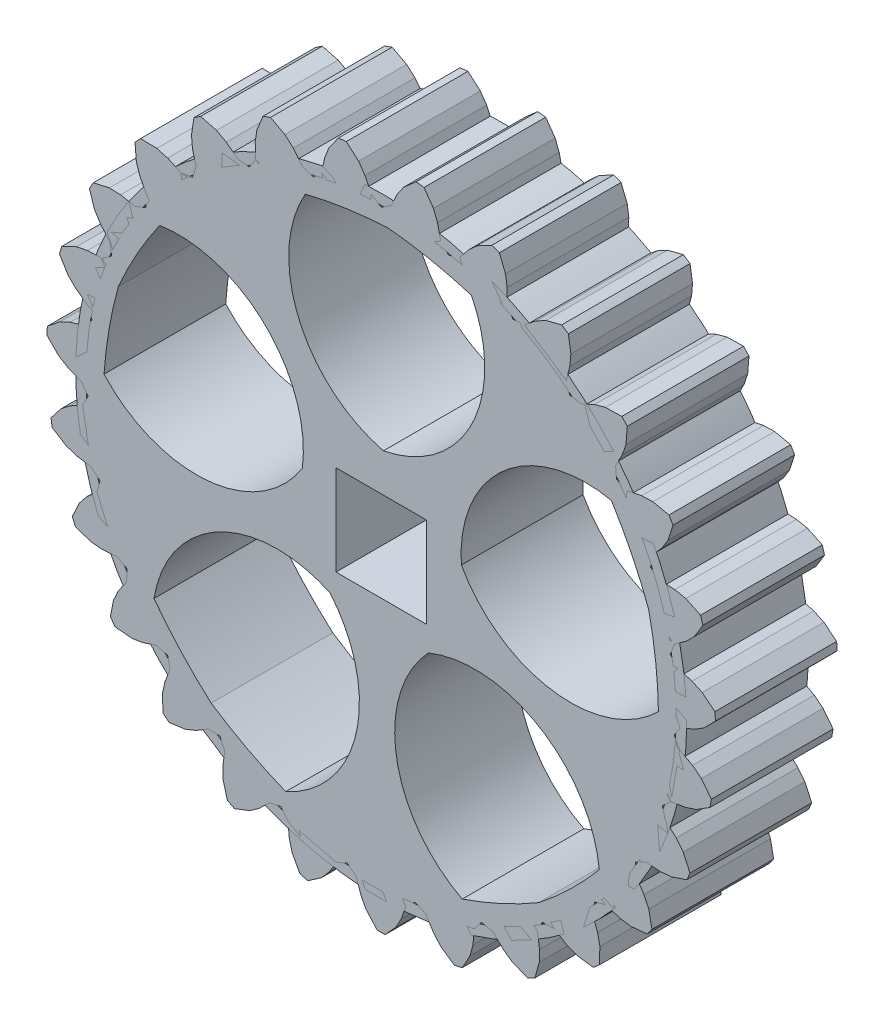
SolidWorks part; units mm, degrees
ref_plane "Front Plane" through (0, 0, 0) normal (0, 0, 1) x (1, 0, 0)
ref_plane "Top Plane" through (0, 0, 0) normal (0, 1, 0) x (1, 0, 0)
ref_plane "Right Plane" through (0, 0, 0) normal (1, 0, 0) x (0, 0, -1)
sketch "Sketch1" plane through (0, 0, 0) normal (0, 0, 1) x (1, 0, 0)
  line L1 (3.7123, -3.7123) -> (-3.7123, -3.7123)
  line L2 (3.7123, -3.7123) -> (3.7123, 3.7123)
  line L3 (3.7123, 3.7123) -> (-3.7123, 3.7123)
  line L4 (-3.7123, -3.7123) -> (-3.7123, 3.7123)
  line L5 (3.7123, -3.7123) -> (-3.7123, 3.7123) construction
  line L6 (3.7123, 3.7123) -> (-3.7123, -3.7123) construction
  circle A0 centre (0, 0) radius 27.5
  circle A1 centre (0, 0) radius 5.25 construction
  dimension "D1" = 55
  dimension "D2" = 10.5
extrude "Boss-Extrude1" add sketch "Sketch1" along normal blind 10
sketch "Sketch2" plane through (0, 0, 0) normal (0, 0, 1) x (1, 0, 0)
  line L0 (0, 0) -> (0, 28.7187) construction
  line L1 (0, 24.1206) -> (-0.8069, 24.6189)
  line L2 (-0.8069, 24.6189) -> (-1.33, 25.7087)
  line L3 (-1.33, 25.7087) -> (-1.8557, 26.4644)
  line L4 (-1.8557, 26.4644) -> (-2.8665, 27.3502)
  line L5 (-2.8665, 27.3502) -> (-1.8557, 28.1227)
  line L6 (-1.8557, 28.1227) -> (0, 28.7187)
  line L7 (1.8557, 28.1227) -> (0, 28.7187)
  line L8 (2.8665, 27.3502) -> (1.8557, 28.1227)
  line L9 (1.8557, 26.4644) -> (2.8665, 27.3502)
  line L10 (1.33, 25.7087) -> (1.8557, 26.4644)
  line L11 (0.8069, 24.6189) -> (1.33, 25.7087)
  line L12 (0, 24.1206) -> (0.8069, 24.6189)
  circle A22 centre (0, 0) radius 27.5 construction
  point P15 (0, 24.1206)
  dimension "D5" = 0.5258
  dimension "D6" = 0.7556
  dimension "D1" = 0.8069
  dimension "D2" = 0.4984
  dimension "D3" = 0.5231
  dimension "D4" = 1.0898
  dimension "D7" = 1.6584
  dimension "D8" = 1.8557
extrude "Cut-Extrude1" cut sketch "Sketch2" along normal through all
pattern_circular "CirPattern1" count 27 over 360 about axis through (0, 0, 0) along (0, 0, 1) of "Cut-Extrude1"
sketch "Sketch3" plane through (0, 0, 0) normal (0, 0, 1) x (1, 0, 0)
  circle A0 centre (0, 0) radius 29.75
  dimension "D1" = 59.5
sketch "Sketch4" plane through (0, 0, 0) normal (0, 0, 1) x (1, 0, 0)
  line L0 (0, 0) -> (0.6245, 22.9095) construction
  arc A0 (0.1872, 6.8675) -> (-6.2369, 21.9201) centre (2.6671, 16.823) cw
  arc A1 (0.6245, 22.9095) -> (-6.2369, 21.9201) centre (2.0438, -11.2177) ccw
  arc A2 (0.6245, 22.9095) -> (7.4217, 21.5478) centre (-2.6519, -11.0897) cw
  arc A3 (0.1872, 6.8675) -> (7.4217, 21.5478) centre (-1.7467, 16.9433) ccw
  point P10 (-8.8069, 21.1994)
  point P11 (-6.0458, 20.2952)
extrude "Cut-Extrude2" cut sketch "Sketch4" along normal through all both
sketch "Sketch5" plane through (0, 0, 0) normal (0, 0, 1) x (1, 0, 0)
  line L0 (3.7123, -3.7123) -> (-3.7123, 3.7123) construction
  circle A0 centre (0, 0) radius 25.1098
  circle A1 centre (0, 0) radius 24.2496
extrude "Boss-Extrude2" add sketch "Sketch5" along normal blind 10 separate body
pattern_circular "CirPattern2" count 5 over 360 about axis through (0, 0, 0) along (0, 0, 1) of "Cut-Extrude2"
chamfer "Chamfer1" distance 0.5 angle 45 4 edges at (-3.7123, 0, 0) (0, -3.7123, 0) (3.7123, 0, 0) (0, 3.7123, 0)
